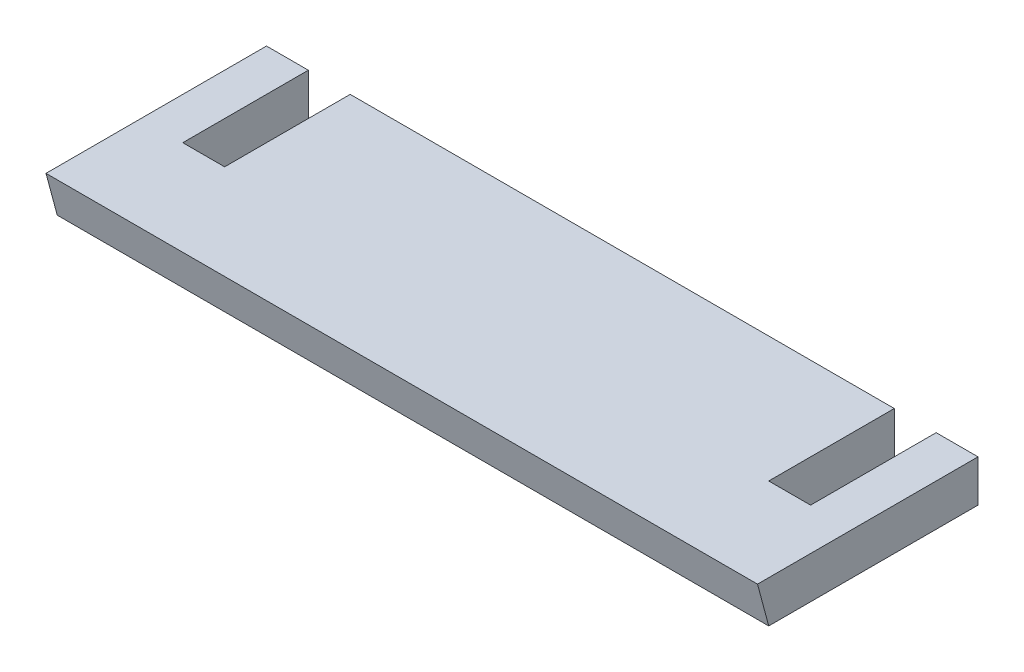
SolidWorks part; units mm, degrees
ref_plane "Front Plane" through (0, 0, 0) normal (0, 0, 1) x (1, 0, 0)
ref_plane "Top Plane" through (0, 0, 0) normal (0, 1, 0) x (1, 0, 0)
ref_plane "Right Plane" through (0, 0, 0) normal (1, 0, 0) x (0, 0, -1)
sketch "Sketch1" plane through (0, 0, 0) normal (0, 1, 0) x (1, 0, 0)
  line L0 (-115.0904, 0) -> (123.4367, 0) construction
  line L1 (0, 70.6137) -> (0, -75.6654) construction
  line L2 (-75, 25) -> (-75, -5)
  line L3 (85, -25) -> (-85, -25)
  line L4 (85, -25) -> (85, 25)
  line L5 (85, 25) -> (75, 25)
  line L6 (-85, -25) -> (-85, 25)
  line L7 (85, -25) -> (-65, 19.1176) construction
  line L8 (85, 25) -> (-85, -25) construction
  line L9 (-75, -5) -> (-65, -5)
  line L10 (-65, -5) -> (-65, 25)
  line L11 (-75, 25) -> (-85, 25)
  line L12 (-75, 22.0588) -> (-85, 25) construction
  line L13 (65, -5) -> (65, 25)
  line L14 (75, -5) -> (65, -5)
  line L15 (75, 25) -> (75, -5)
  line L16 (65, 25) -> (-65, 25)
  point P5 (0, 0)
  dimension "D1" = 170
  dimension "D2" = 50
  dimension "D3" = 10
  dimension "D4" = 30
  dimension "D5" = 10
extrude "Boss-Extrude1" add sketch "Sketch1" along normal blind 10
draft "Draft2" type of draft neutral plane draft angle 15 faces to draft 1 face at (0, 5, 25) neutral plane through (0, 0, 0) neutral plane normal (0, -1, 0) parameters "D1"=15
